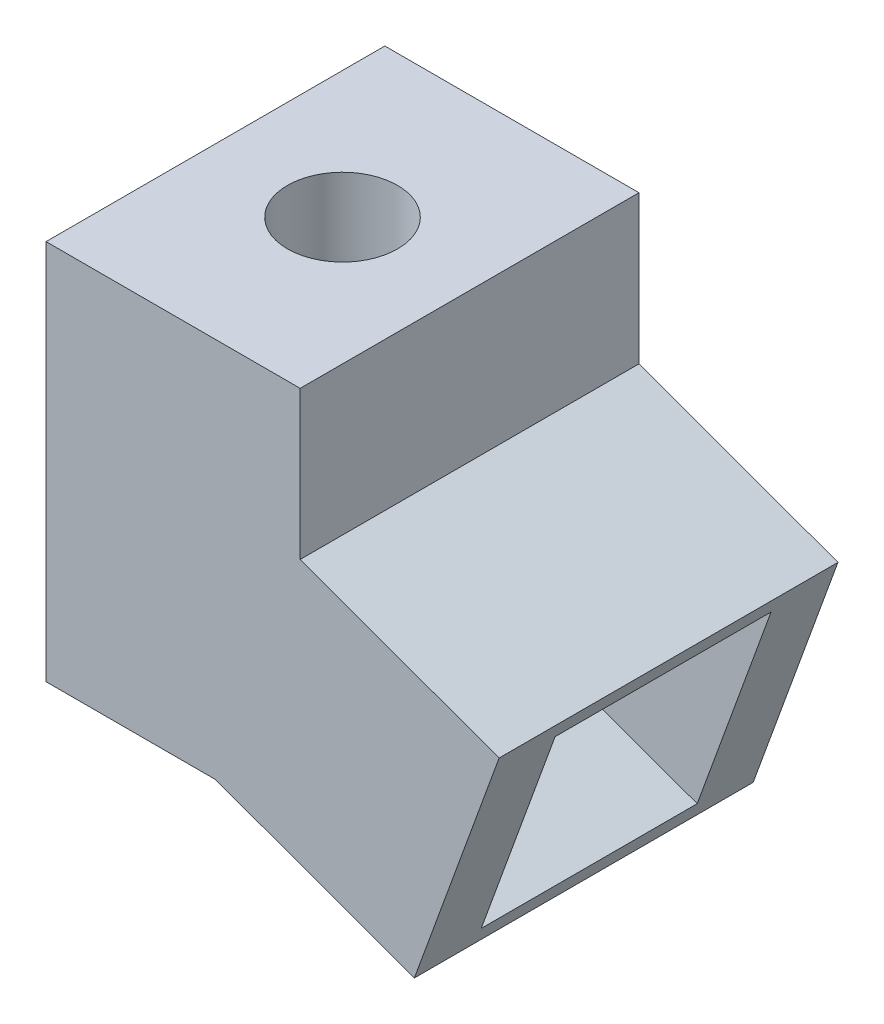
SolidWorks part; units mm, degrees
ref_plane "前视基准面" through (0, 0, 0) normal (0, 0, 1) x (1, 0, 0)
ref_plane "上视基准面" through (0, 0, 0) normal (0, 1, 0) x (1, 0, 0)
ref_plane "右视基准面" through (0, 0, 0) normal (1, 0, 0) x (0, 0, -1)
other "Configuration Table"
sketch "草图1" plane through (0, 0, 0) normal (0, 1, 0) x (1, 0, 0)
  line L0 (7.5, 5) -> (7.5, 0) construction
  line L1 (0, 0) -> (15, 0)
  line L2 (0, 0) -> (0, 5)
  line L3 (0, 5) -> (15, 5)
  line L4 (15, 0) -> (15, 5)
  circle A0 centre (3.25, 2.5) radius 0.85
  circle A1 centre (11.75, 2.5) radius 0.85
  point P12 (0, 2.5)
  dimension "D3" = 1.7
  dimension "D1" = 15
  dimension "D2" = 5
  dimension "D4" = 8.5
extrude "凸台-拉伸1" add sketch "草图1" along normal blind 2 contours L2 L1 L4 L3 | A0 | A1
sketch "草图2" plane through (0, 0, 0) normal (0, -1, 0) x (1, 0, 0)
  line L7 (0, 0) -> (15, 0) construction
  line L9 (0, -5) -> (15, -5) construction
  line L11 (7.5, 0) -> (7.5, -5) construction
  line L13 (10.5, 1.5) -> (4.5, 1.5)
  line L14 (4.5, 1.5) -> (4.5, -6.5)
  line L16 (10.5, 1.5) -> (10.5, -6.5)
  line L17 (0, -2.5) -> (15, -2.5) construction
  line L18 (0, 0) -> (0, -5) construction
  line L19 (15, 0) -> (15, -5) construction
  line L20 (10.5, -6.5) -> (4.5, -6.5)
  point P11 (7.5, 1.5)
  point P12 (7.5, -6.9299)
  dimension "D1" = 6
  dimension "D2" = 8
extrude "凸台-拉伸3" add sketch "草图2" along normal blind 6
sketch "草图6" plane through (0, 0, -6.5) normal (0, 0, -1) x (-1, 0, 0)
  line L0 (-10.5, -0.5) -> (-10.5, -6)
  line L1 (-10.5, -6) -> (-10.5, 0) construction
  line L2 (-10.5, -6) -> (-8.4982, -6)
  line L3 (-4.5, -6) -> (-10.5, -6) construction
  line L4 (-8.4982, -6) -> (-10.5, -0.5)
  dimension "D1" = 20
  dimension "D2" = 5.5
extrude "切除-拉伸2" cut sketch "草图6" against normal up to surface (8 mm away) up to face at (7.5, -3, 1.5)
sketch "草图7" plane through (9.4324, -3.4331, 0) normal (0.9397, -0.342, 0) x (0, 0, -1)
  line L0 (-1.5, 0.1949) -> (6.5, 0.1949) construction
  line L1 (-1.5, 3.1214) -> (-1.5, -2.7316) construction
  line L2 (6.5, -2.7316) -> (6.5, 3.1214) construction
  line L3 (5.05, 2.7449) -> (-0.05, 2.7449)
  line L4 (-1.5, 3.1214) -> (6.5, 3.1214) construction
  line L5 (2.5, 3.1214) -> (2.5, -2.7316) construction
  line L6 (-1.5, -2.7316) -> (6.5, -2.7316) construction
  line L7 (-0.05, 2.7449) -> (-0.05, -2.3551)
  line L8 (5.05, -2.3551) -> (-0.05, -2.3551)
  line L9 (5.05, 2.7449) -> (5.05, -2.3551)
  point P16 (-0.05, 0.1949)
  point P18 (2.5, -2.3551)
  point P19 (2.5, 2.7449)
  dimension "D1" = 5.1
  dimension "D2" = 5.1
extrude "切除-拉伸3" cut sketch "草图7" against normal blind 2
sketch "草图10" plane through (9.4324, -3.4331, 0) normal (0.9397, -0.342, 0) x (0, 0, -1)
  line L1 (-0.05, 2.7449) -> (5.05, 2.7449)
  line L2 (-0.05, 2.7449) -> (-0.05, -2.3551)
  line L3 (-0.05, -2.3551) -> (5.05, -2.3551)
  line L4 (5.05, 2.7449) -> (5.05, -2.3551)
  line L5 (-1.5, 3.1214) -> (6.5, 3.1214)
  line L6 (-1.5, 3.1214) -> (-1.5, -2.7316)
  line L7 (-1.5, -2.7316) -> (6.5, -2.7316)
  line L8 (6.5, 3.1214) -> (6.5, -2.7316)
extrude "凸台-拉伸4" add sketch "草图10" along normal blind 5
sketch "草图11" plane through (0, 0, 0) normal (0, 1, 0) x (1, 0, 0)
  line L1 (4.5, 6.5) -> (10.5, 6.5)
  line L2 (4.5, 6.5) -> (4.5, -1.5)
  line L3 (4.5, -1.5) -> (10.5, -1.5)
  line L4 (10.5, 6.5) -> (10.5, -1.5)
extrude "凸台-拉伸5" add sketch "草图11" along normal blind 3
sketch "草图12" plane through (0, 3, 0) normal (0, 1, 0) x (1, 0, 0)
  line L0 (4.5, 2.5) -> (10.5, 2.5)
  line L1 (4.5, 6.5) -> (4.5, -1.5) construction
  line L2 (10.5, 5) -> (10.5, 0) construction
  circle A0 centre (7.5, 2.5) radius 1.3
  dimension "D1" = 2.6
extrude "切除-拉伸4" cut sketch "草图12" against normal blind 5 contours L0 A0 | L0 A0
sketch "草图13" plane through (0, 2, 0) normal (0, 1, 0) x (1, 0, 0)
  line L1 (0, 5) -> (4.5, 5)
  line L2 (0, 5) -> (0, 0)
  line L3 (0, 0) -> (4.5, 0)
  line L4 (4.5, 5) -> (4.5, 0)
  line L5 (10.5, 5) -> (15, 5)
  line L6 (10.5, 5) -> (10.5, 0)
  line L7 (10.5, 0) -> (15, 0)
  line L8 (15, 5) -> (15, 0)
extrude "切除-拉伸5" cut sketch "草图13" against normal up to surface (2 mm away) up to face at (11.75, 0, -3.35)
